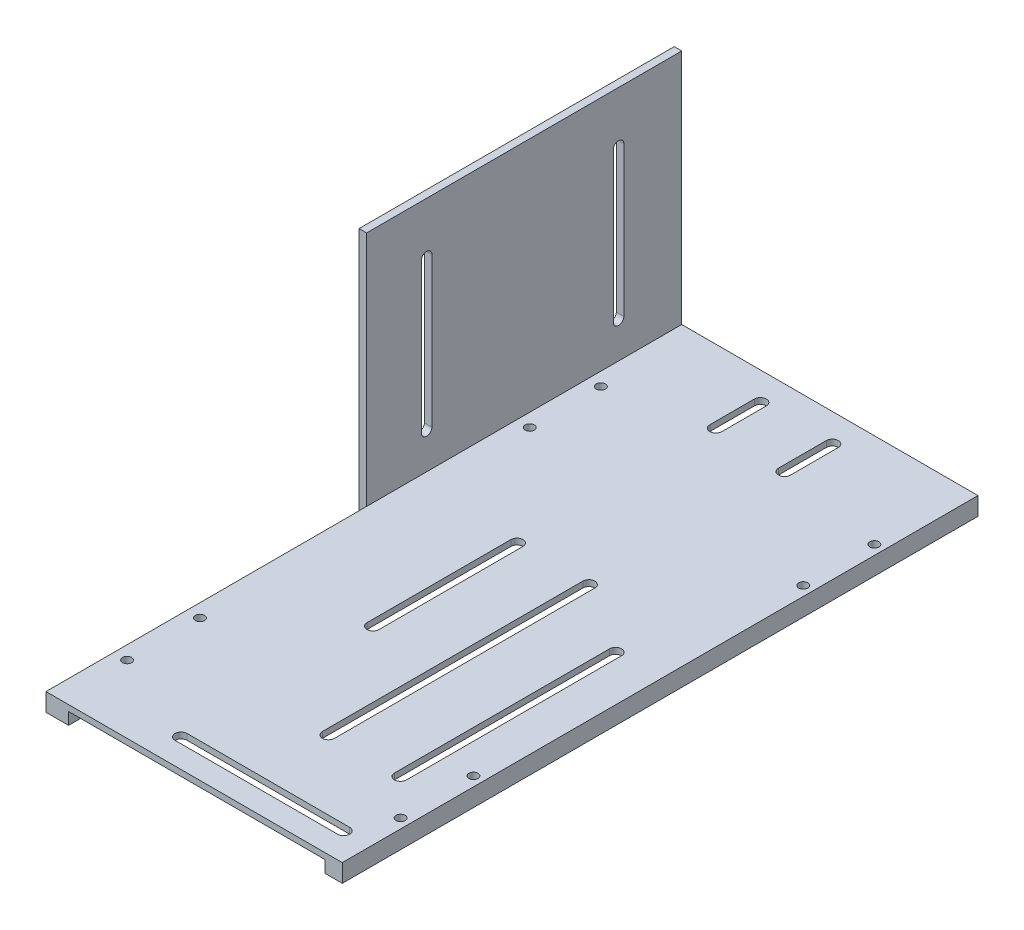
SolidWorks part; units mm, degrees
ref_plane "Front Plane" through (0, 0, 0) normal (0, 0, 1) x (1, 0, 0)
ref_plane "Top Plane" through (0, 0, 0) normal (0, 1, 0) x (1, 0, 0)
ref_plane "Right Plane" through (0, 0, 0) normal (1, 0, 0) x (0, 0, -1)
sketch "草图1" plane through (0, 0, 0) normal (0, 1, 0) x (1, 0, 0)
  line L2 (0, 200.0862) -> (70.1538, 200.0862)
  line L3 (99.7709, 107.0806) -> (99.7709, 0.0862)
  line L4 (61.2124, -4.4895) -> (6.978, -4.4895)
  line L5 (8.978, 109.4975) -> (8.978, 61.5185)
  line L6 (0, 200.0862) -> (6.978, 200.0862)
  line L8 (4.978, 190.6837) -> (4.978, 175.8503)
  line L9 (8.978, 190.6837) -> (8.978, 175.8503)
  line L10 (32.978, 190.6837) -> (32.978, 174.7296)
  line L11 (28.978, 190.6837) -> (28.978, 174.7296)
  line L12 (56.978, 94.3935) -> (56.978, 22.6647)
  line L13 (52.978, 94.3935) -> (52.978, 22.6647)
  line L16 (4.978, 109.4975) -> (4.978, 61.5185)
  line L17 (28.978, 109.4975) -> (28.978, 22.6647)
  line L18 (32.978, 109.4975) -> (32.978, 22.6647)
  line L23 (70.1538, 107.0806) -> (70.1538, 200.0862)
  line L24 (-24.222, 145) -> (-24.222, 143.475)
  line L26 (-28.6425, 0.0862) -> (-28.6425, -11.9138)
  line L27 (-28.6425, -11.9138) -> (70.1538, -11.9138)
  line L28 (99.7709, -11.9138) -> (99.7709, 0.0862)
  line L29 (-28.6425, 0.0862) -> (-28.6425, 200.0862)
  line L30 (-28.6425, 200.0862) -> (-10.0336, 200.0862)
  line L31 (-10.0336, 200.0862) -> (0, 200.0862)
  line L32 (-22.697, 145) -> (-24.222, 145)
  line L35 (61.2124, -0.4895) -> (56.978, -0.4895)
  line L39 (28.978, -0.4895) -> (8.978, -0.4895)
  line L40 (52.978, -0.4895) -> (32.978, -0.4895)
  line L43 (70.1538, 107.0806) -> (70.1538, -11.9138)
  line L44 (80.978, 67.5105) -> (80.978, 7.5105) [skipped]
  line L45 (76.978, 67.5105) -> (76.978, 7.5105) [skipped]
  line L46 (8.978, -0.4895) -> (6.978, -0.4895)
  line L47 (56.978, -0.4895) -> (52.978, -0.4895)
  line L48 (32.978, -0.4895) -> (28.978, -0.4895)
  arc A7 (8.978, 190.6837) -> (4.978, 190.6837) centre (6.978, 190.6837) ccw
  arc A9 (32.978, 190.6837) -> (28.978, 190.6837) centre (30.978, 190.6837) ccw
  arc A19 (80.978, 190.6837) -> (76.978, 190.6837) centre (78.978, 190.6837) ccw [skipped]
  arc A20 (56.978, 94.3935) -> (52.978, 94.3935) centre (54.978, 94.3935) ccw
  arc A21 (56.978, 190.6837) -> (52.978, 190.6837) centre (54.978, 190.6837) ccw [skipped]
  arc A22 (28.978, 174.7296) -> (32.978, 174.7296) centre (30.978, 174.7296) ccw
  arc A23 (32.978, 109.4975) -> (28.978, 109.4975) centre (30.978, 109.4975) ccw
  arc A24 (4.978, 175.8503) -> (8.978, 175.8503) centre (6.978, 175.8503) ccw
  arc A25 (8.978, 109.4975) -> (4.978, 109.4975) centre (6.978, 109.4975) ccw
  arc A26 (4.978, 61.5185) -> (8.978, 61.5185) centre (6.978, 61.5185) ccw
  circle A29 centre (-24.222, 145) radius 1.525
  circle A32 centre (66.978, 145) radius 1.525
  circle A33 centre (66.978, 35) radius 1.525
  circle A34 centre (-24.222, 35) radius 1.525
  circle A35 centre (-24.222, 10.7015) radius 1.525
  circle A36 centre (66.978, 10.7015) radius 1.525
  circle A37 centre (66.978, 168.7015) radius 1.525
  circle A38 centre (-24.222, 168.7015) radius 1.525
  arc A41 (6.978, -0.4895) -> (6.978, -4.4895) centre (6.978, -2.4895) ccw
  arc A42 (52.978, 22.6647) -> (56.978, 22.6647) centre (54.978, 22.6647) ccw
  arc A43 (28.978, 22.6647) -> (32.978, 22.6647) centre (30.978, 22.6647) ccw
  arc A44 (61.2124, -4.4895) -> (61.2124, -0.4895) centre (61.2124, -2.4895) ccw
  dimension "D1" = 4
  dimension "D4" = 2
  dimension "D6" = 2
  dimension "D5" = 2
  dimension "D7" = 2
extrude "凸台-拉伸1" add sketch "草图1" along normal blind 6
sketch "草图4" plane through (0, 0, 0) normal (0, -1, 0) x (1, 0, 0)
  line L0 (-28.6425, -200.0862) -> (-28.6425, -95)
  line L2 (-28.6425, 11.9138) -> (-28.6425, -200.0862) construction
  line L3 (-28.6425, -95) -> (-31.1425, -95)
  line L4 (-31.1425, -95) -> (-31.1425, -200.0862)
  line L5 (-31.1425, -200.0862) -> (-28.6425, -200.0862)
extrude "凸台-拉伸3" add sketch "草图4" against normal blind 85 contours L4 L5 L0 L3
sketch "草图3" plane through (-28.6425, 0, 0) normal (1, 0, 0) x (0, 0, -1)
  line L0 (115.023, 16.25) -> (115.023, 18)
  line L2 (113.273, 18) -> (113.273, 67.893)
  line L3 (116.773, 67.893) -> (116.773, 18)
  line L4 (115.023, 35.893) -> (116.773, 35.893)
  line L5 (177.273, 35.893) -> (179.023, 35.893)
  line L6 (180.773, 18) -> (180.773, 67.893)
  line L7 (177.273, 67.893) -> (177.273, 18)
  arc A0 (116.773, 67.893) -> (113.273, 67.893) centre (115.023, 67.893) ccw
  arc A1 (180.773, 67.893) -> (177.273, 67.893) centre (179.023, 67.893) ccw
  arc A4 (113.273, 18) -> (116.773, 18) centre (115.023, 18) ccw
  arc A5 (180.773, 18) -> (177.273, 18) centre (179.023, 18) cw
  arc A6 (113.273, 35.893) -> (116.773, 35.893) centre (115.023, 35.893) ccw [skipped]
  arc A7 (180.773, 35.893) -> (177.273, 35.893) centre (179.023, 35.893) ccw [skipped]
  dimension "D1" = 2
  dimension "D2" = 2
extrude "切除-拉伸1" cut sketch "草图3" against normal blind 58
sketch "草图5" plane through (0, 0, 0) normal (0, -1, 0) x (1, 0, 0)
  line L0 (-28.6425, 11.9138) -> (70.1538, 11.9138) construction
  line L1 (-21.0993, 11.9138) -> (64.4178, 11.9138)
  line L2 (-21.0993, 11.9138) -> (-21.0993, -200.0862)
  line L3 (-21.0993, -200.0862) -> (64.4178, -200.0862)
  line L4 (64.4178, 11.9138) -> (64.4178, -200.0862)
  line L5 (-31.1425, -200.0862) -> (70.1538, -200.0862) construction
extrude "切除-拉伸2" cut sketch "草图5" against normal blind 4
